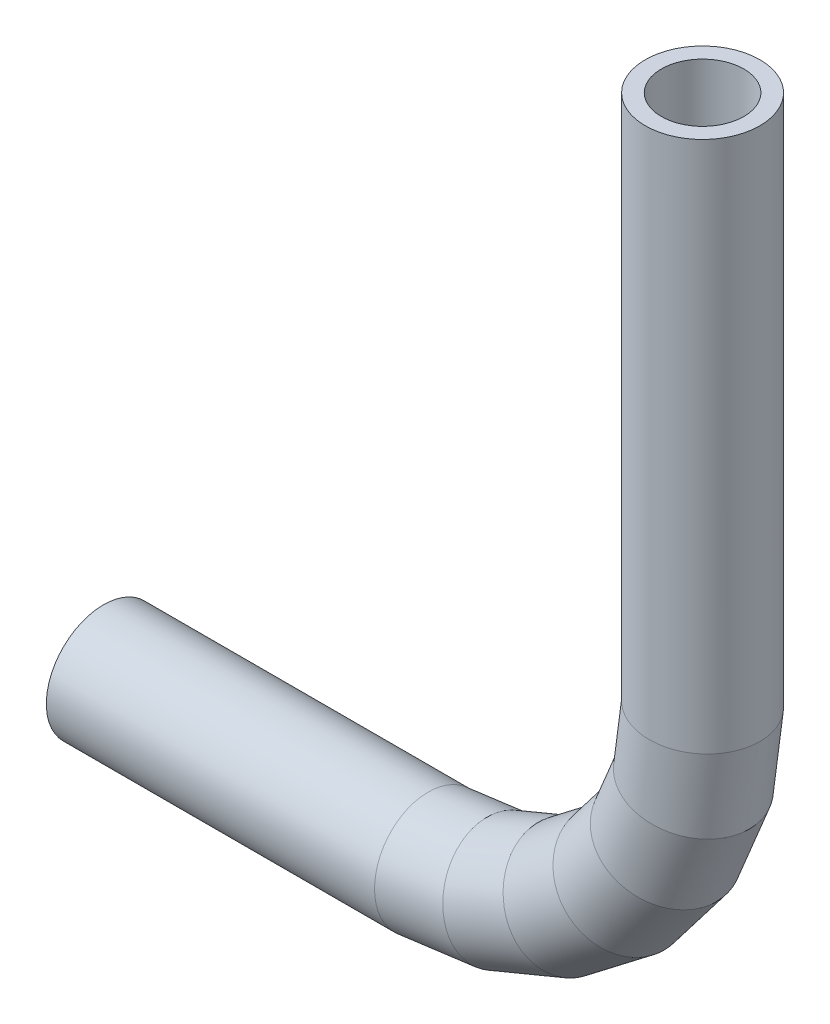
SolidWorks part; units mm, degrees
ref_plane "Front Plane" through (0, 0, 0) normal (0, 0, 1) x (1, 0, 0)
ref_plane "Top Plane" through (0, 0, 0) normal (0, 1, 0) x (1, 0, 0)
ref_plane "Right Plane" through (0, 0, 0) normal (1, 0, 0) x (0, 0, -1)
sketch3d "Path"
  line L0 (-520.7, 36, 0) -> (-502.5, 36, 0)
  line L1 (-502.5, 36, 0) -> (-498.6177, 36.5111, 0)
  line L2 (-498.6177, 36.5111, 0) -> (-495, 38.0096, 0)
  line L3 (-495, 38.0096, 0) -> (-491.8934, 40.3934, 0)
  line L4 (-491.8934, 40.3934, 0) -> (-489.5096, 43.5, 0)
  line L5 (-489.5096, 43.5, 0) -> (-488.0111, 47.1177, 0)
  line L6 (-488.0111, 47.1177, 0) -> (-487.5, 51, 0)
  line L7 (-487.5, 51, 0) -> (-487.5, 80.35, 0)
ref_plane "Start Plane" through (-520.7, 0, 0) normal (1, 0, 0) x (0, 0, -1)
sketch "Profile" plane through (-520.7, 0, 0) normal (1, 0, 0) x (0, 0, -1)
  circle A0 centre (0, 36) radius 3.175
  circle A1 centre (0, 36) radius 2.286
sweep "Tube" add profiles "Profile" path "Path"
